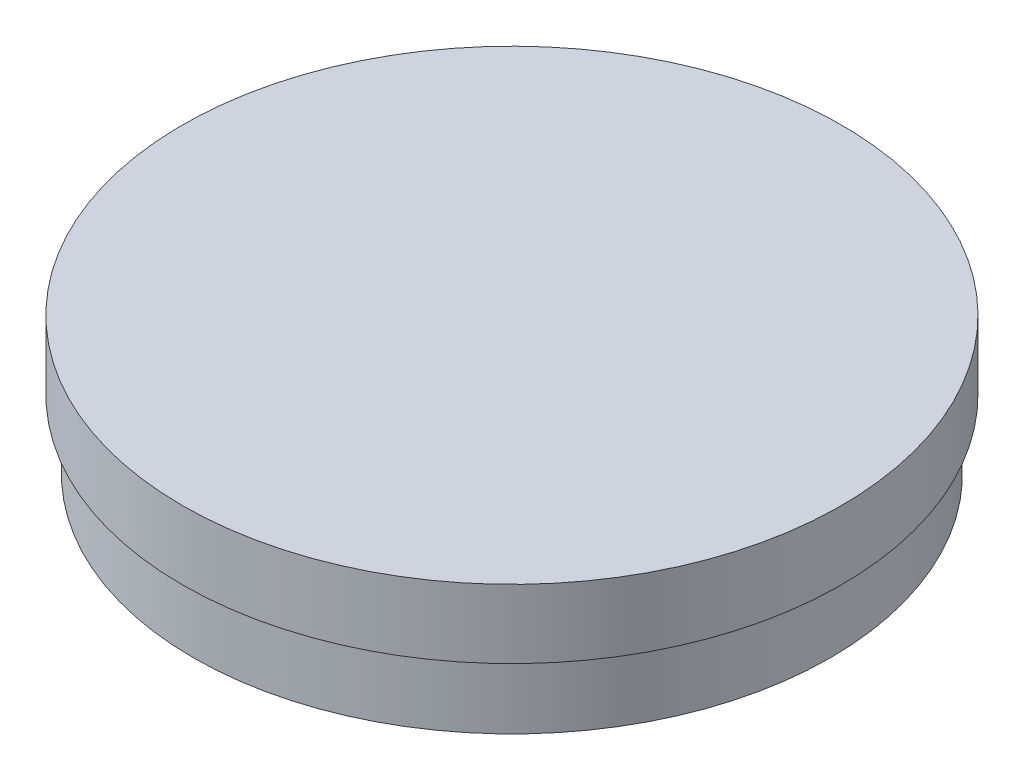
SolidWorks part; units mm, degrees
ref_plane "Front Plane" through (0, 0, 0) normal (0, 0, 1) x (1, 0, 0)
ref_plane "Top Plane" through (0, 0, 0) normal (0, 1, 0) x (1, 0, 0)
ref_plane "Right Plane" through (0, 0, 0) normal (1, 0, 0) x (0, 0, -1)
sketch "Sketch1" plane through (0, 0, 0) normal (0, 0, 1) x (1, 0, 0)
  line L0 (0, 53.1607) -> (0, -48.5179) construction
  line L1 (0, 48.0536) -> (120, 48.0536)
  line L2 (120, 48.0536) -> (120, 23.0536)
  line L3 (120, 23.0536) -> (116, 23.0536)
  line L4 (116, 23.0536) -> (116, -1.9464)
  line L5 (116, -1.9464) -> (0, -1.9464)
  line L6 (0, -1.9464) -> (0, 48.0536)
  dimension "D1" = 120
  dimension "D2" = 25
  dimension "D3" = 25
  dimension "D4" = 4
revolve "Revolve1" add sketch "Sketch1" angle 360 about L0
